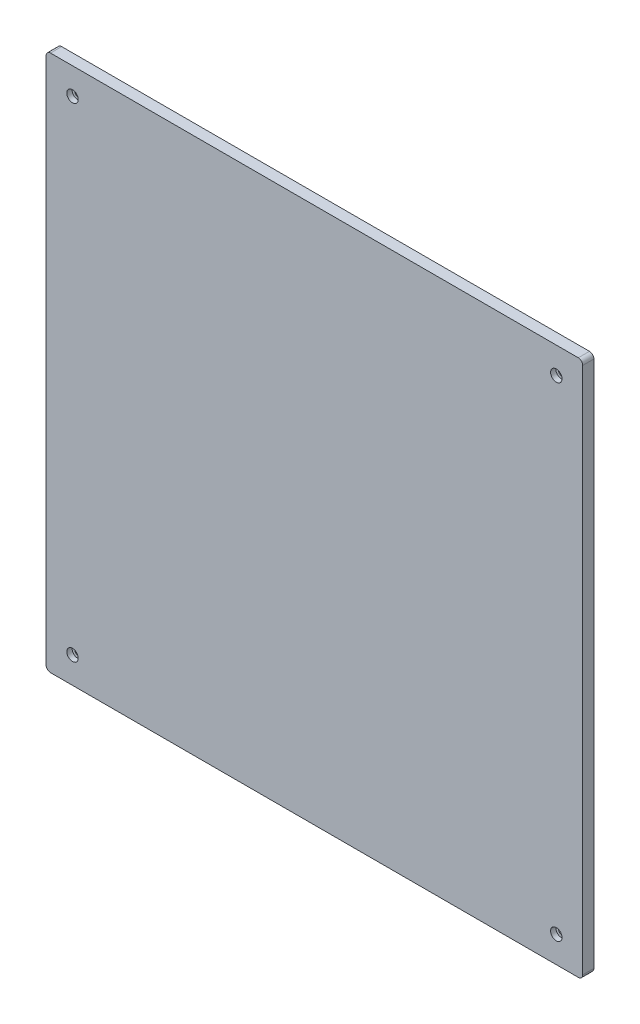
SolidWorks part; units mm, degrees
ref_plane "Front Plane" through (0, 0, 0) normal (0, 0, 1) x (1, 0, 0)
ref_plane "Top Plane" through (0, 0, 0) normal (0, 1, 0) x (1, 0, 0)
ref_plane "Right Plane" through (0, 0, 0) normal (1, 0, 0) x (0, 0, -1)
sketch "Sketch1" plane through (0, 0, 0) normal (0, 0, 1) x (1, 0, 0)
  line L1 (-152.4, -152.4) -> (152.4, -152.4)
  line L2 (-152.4, -152.4) -> (-152.4, 152.4)
  line L3 (-152.4, 152.4) -> (152.4, 152.4)
  line L4 (152.4, -152.4) -> (152.4, 152.4)
  line L5 (-152.4, -152.4) -> (152.4, 152.4) construction
  line L6 (-152.4, 152.4) -> (152.4, -152.4) construction
  point P0 (0, 0)
  dimension "D1" = 304.8
  dimension "D2" = 304.8
extrude "Boss-Extrude1" add sketch "Sketch1" along normal blind 6.35
hole_wizard "CBORE for M3 SHCS1" positions "Sketch2" profile "Sketch3" counterbore size "M3" standard "ANSI Metric" end condition up to next
sketch "Sketch2" plane through (0, 0, 6.35) normal (0, 0, 1) x (1, 0, 0)
  line L0 (152.4, -152.4) -> (152.4, 152.4) construction
  line L1 (152.4, 152.4) -> (-152.4, 152.4) construction
  line L2 (-152.4, -152.4) -> (152.4, -152.4) construction
  line L3 (-152.4, 152.4) -> (-152.4, -152.4) construction
  point P0 (137.4, 137.4)
  point P2 (-137.4, -137.4)
  point P4 (137.4, -137.4)
  point P6 (-137.4, 137.4)
  dimension "D1" = 15
  dimension "D2" = 15
  dimension "D3" = 15
  dimension "D4" = 15
sketch "Sketch3" plane through (137.4, 137.4, 6.35) normal (1, 0, 0) x (0, -1, 0)
  line L0 (0, 0) -> (0, 6.35)
  line L1 (0, 6.35) -> (1.7, 6.35)
  line L3 (1.7, 6.35) -> (1.7, 3)
  line L4 (1.7, 3) -> (3.25, 3)
  line L5 (3.25, 3) -> (3.25, 0)
  line L7 (3.25, 0) -> (0, 0)
  line L11 (0, -6.35) -> (0, 107.95) construction
  dimension "Thru Hole Dia." = 3.4
  dimension "Thru Hole Depth" = 6.35
  dimension "C'Bore Dia." = 6.5
  dimension "C'Bore Depth" = 3
fillet "Fillet1" radius 2.5 4 edges at (152.4, 152.4, 3.175) (152.4, -152.4, 3.175) (-152.4, -152.4, 3.175) (-152.4, 152.4, 3.175)
